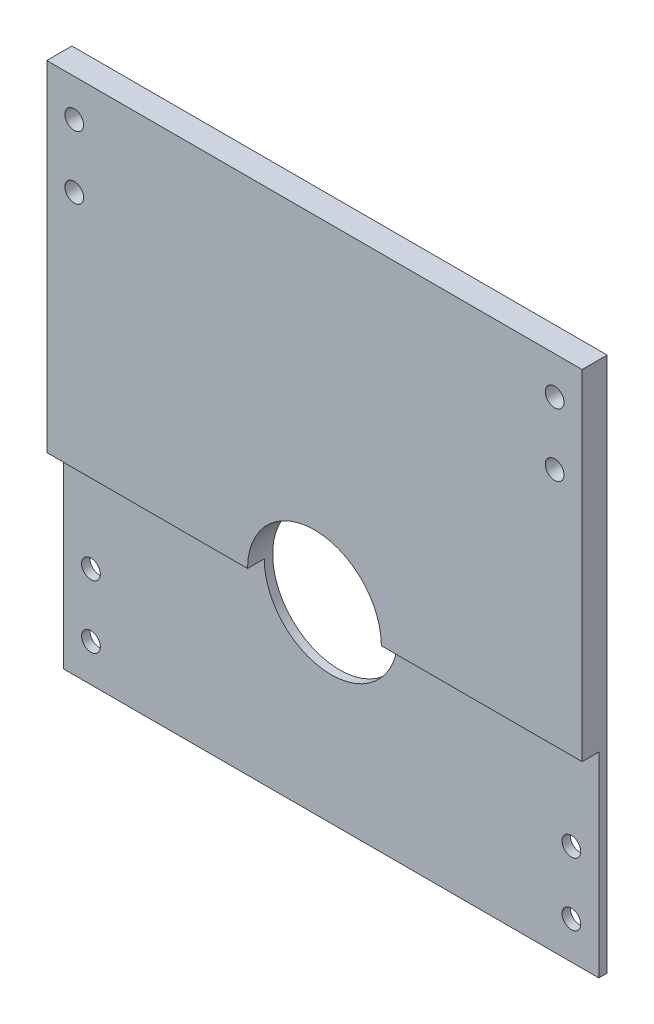
SolidWorks part; units mm, degrees
ref_plane "前视基准面" through (0, 0, 0) normal (0, 0, 1) x (1, 0, 0)
ref_plane "上视基准面" through (0, 0, 0) normal (0, 1, 0) x (1, 0, 0)
ref_plane "右视基准面" through (0, 0, 0) normal (1, 0, 0) x (0, 0, -1)
sketch "草图1" plane through (0, 0, 0) normal (0, 0, 1) x (1, 0, 0)
  line L0 (0, -203.2) -> (0, -54.602) construction
  line L1 (-203.2, 203.2) -> (203.2, 203.2)
  line L2 (-203.2, 203.2) -> (-203.2, -203.2)
  line L3 (-203.2, -203.2) -> (203.2, -203.2)
  line L4 (203.2, 203.2) -> (203.2, -203.2)
  line L5 (0, -54.602) -> (-203.2, -54.602) construction
  line L6 (0, -54.602) -> (203.2, -54.602) construction
  circle A0 centre (0, -54.602) radius 50.8
  dimension "D1" = 148.598
  dimension "D2" = 406.4
  dimension "D4" = 406.4
extrude "凸台-拉伸1" add sketch "草图1" along normal blind 19.05
ref_plane "基准面1" through (0, 0, 19.05) normal (0, 0, 1) x (1, 0, 0)
sketch "草图3" plane through (0, 0, 19.05) normal (0, 0, 1) x (1, 0, 0)
  line L0 (0, -54.602) -> (-203.2, -54.602) construction
  line L1 (-203.2, 203.2) -> (-203.2, -203.2) construction
  line L2 (-50.8, -54.602) -> (-203.2, -54.602)
  line L3 (-203.2, -54.602) -> (-203.2, -203.2)
  line L4 (-203.2, -203.2) -> (203.2, -203.2)
  line L5 (203.2, -203.2) -> (203.2, -54.602)
  line L6 (203.2, -203.2) -> (203.2, 203.2) construction
  line L7 (203.2, -54.602) -> (50.8, -54.602)
  arc A0 (-50.8, -54.602) -> (50.8, -54.602) centre (0, -54.602) ccw
extrude "切除-拉伸1" cut sketch "草图3" against normal blind 12.7
sketch "草图4" plane through (0, 0, 0) normal (0, 0, 1) x (1, 0, 0)
  line L0 (0, 203.2) -> (0, -203.2) construction
  line L1 (203.2, 203.2) -> (-203.2, 203.2) construction
  line L2 (-203.2, 174.752) -> (-182.372, 174.752) construction
  line L3 (-203.2, -203.2) -> (203.2, -203.2) construction
  line L4 (-203.2, 203.2) -> (-203.2, -54.602) construction
  line L5 (-182.372, 174.752) -> (-182.372, 203.2) construction
  line L6 (-182.372, 174.752) -> (-182.372, 127) construction
  line L7 (0, 0) -> (-203.2, 0) construction
  line L8 (0, 0) -> (203.2, 0) construction
  line L9 (203.2, -54.602) -> (203.2, 203.2) construction
  circle A0 centre (-182.372, 174.752) radius 7.112
  circle A1 centre (-182.372, 127) radius 7.112
  circle A2 centre (182.372, 127) radius 7.112
  circle A3 centre (182.372, 174.752) radius 7.112
  circle A4 centre (182.372, -174.752) radius 7.112
  circle A5 centre (182.372, -127) radius 7.112
  circle A6 centre (-182.372, -174.752) radius 7.112
  circle A7 centre (-182.372, -127) radius 7.112
  dimension "D1" = 28.448
  dimension "D2" = 20.828
  dimension "D3" = 47.752
extrude "切除-拉伸4" cut sketch "草图4" along normal through all
